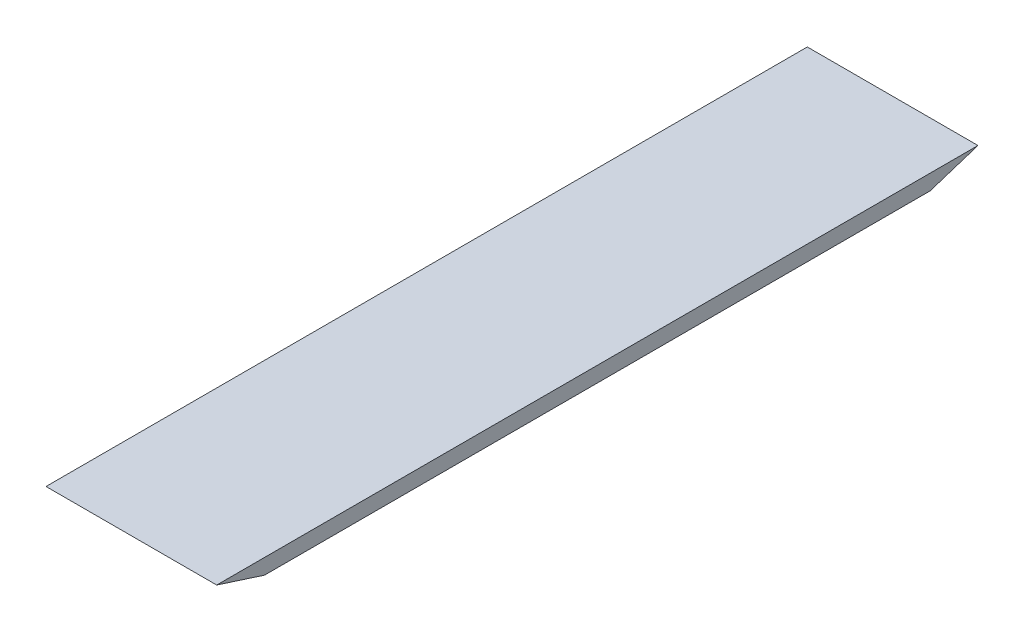
SolidWorks part; units mm, degrees
ref_plane "Front Plane" through (0, 0, 0) normal (0, 0, 1) x (1, 0, 0)
ref_plane "Top Plane" through (0, 0, 0) normal (0, 1, 0) x (1, 0, 0)
ref_plane "Right Plane" through (0, 0, 0) normal (1, 0, 0) x (0, 0, -1)
sketch "Sketch1" plane through (0, 0, 0) normal (1, 0, 0) x (0, 0, -1)
  line L0 (0, 0) -> (446, 0)
  line L1 (446, 0) -> (418, -9)
  line L2 (418, -9) -> (28, -9)
  line L3 (28, -9) -> (0, 0)
  dimension "D1" = 390
  dimension "D2" = 28
  dimension "D3" = 28
  dimension "D4" = 9
extrude "Boss-Extrude1" add sketch "Sketch1" along normal blind 100 contours L2 L3 L0 L1
